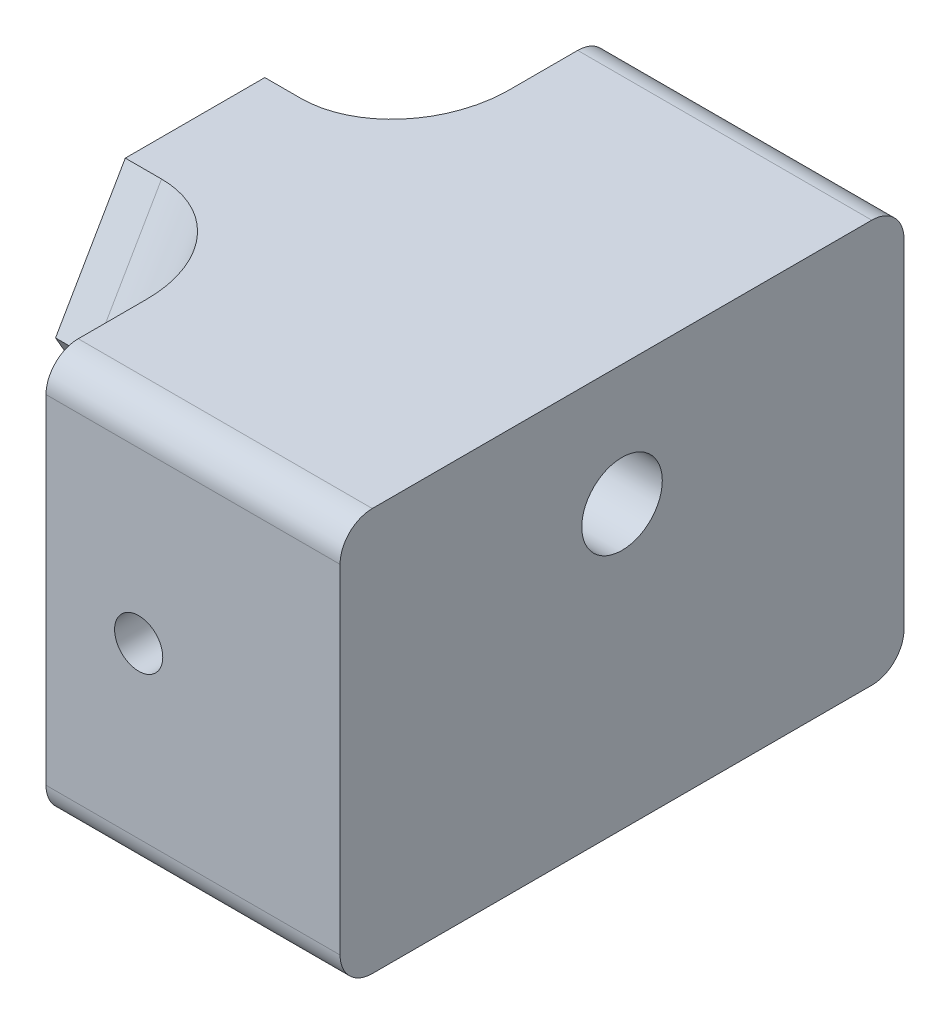
SolidWorks part; units mm, degrees
material "ABS"
ref_plane "Front Plane" through (0, 0, 0) normal (0, 0, 1) x (1, 0, 0)
ref_plane "Top Plane" through (0, 0, 0) normal (0, 1, 0) x (1, 0, 0)
ref_plane "Right Plane" through (0, 0, 0) normal (1, 0, 0) x (0, 0, -1)
sketch "Sketch1" plane through (0, 0, 0) normal (1, 0, 0) x (0, 0, -1)
  line L1 (0, 0) -> (44.45, 0)
  line L2 (0, 0) -> (0, -31.75)
  line L3 (0, -31.75) -> (44.45, -31.75)
  line L4 (44.45, 0) -> (44.45, -31.75)
  dimension "D1" = 44.45
  dimension "D2" = 31.75
extrude "Boss-Extrude1" add sketch "Sketch1" along normal blind 25.4 and the other way blind 8.255
sketch "Sketch2" plane through (-8.255, 0, 0) normal (-1, 0, 0) x (0, 0, 1)
  line L0 (0, 0) -> (0, -31.75) construction
  line L1 (-18.5588, -15.875) -> (-14.8927, -9.525)
  line L2 (-14.8927, -9.525) -> (-18.5588, -3.175)
  line L3 (-18.5588, -3.175) -> (-25.8912, -3.175)
  line L4 (-25.8912, -3.175) -> (-29.5573, -9.525)
  line L5 (-29.5573, -9.525) -> (-25.8912, -15.875)
  line L6 (-25.8912, -15.875) -> (-18.5588, -15.875)
  line L7 (-44.45, 0) -> (0, 0) construction
  circle A0 centre (-22.225, -9.525) radius 6.35 construction
  point P1 (0, -15.875)
  point P13 (-22.225, 0)
  dimension "D1" = 12.7
  dimension "D2" = 9.525
extrude "Cut-Extrude1" cut sketch "Sketch2" against normal blind 7.9375
sketch "Sketch3" plane through (25.4, 0, 0) normal (1, 0, 0) x (0, 0, -1)
  line L0 (44.45, 0) -> (0, 0) construction
  line L1 (0, 0) -> (0, -31.75) construction
  circle A0 centre (22.225, -9.525) radius 3.175
  point P2 (22.225, 0)
  point P3 (0, -15.875)
  dimension "D1" = 6.35
  dimension "D2" = 9.525
extrude "Cut-Extrude2" cut sketch "Sketch3" against normal through all
sketch "Sketch4" plane through (0, 0, 0) normal (0, 0, 1) x (1, 0, 0)
  line L0 (25.4, -15.875) -> (9.525, -15.875) construction
  line L1 (25.4, 0) -> (25.4, -31.75) construction
  circle A2 centre (9.525, -15.875) radius 1.8986
  dimension "D2" = 3.7973
  dimension "D1" = 15.875
ref_plane "Plane1" through (0, 0, -22.225) normal (0, 0, 1) x (1, 0, 0)
extrude "Cut-Extrude4" cut sketch "Sketch4" against normal blind 4.7625
mirror "Mirror3" about plane through (0, 0, -22.225) normal (0, 0, 1) of "Cut-Extrude4"
ref_plane "Plane2" through (25.4, 0, -44.45) normal (-1, 0, 0) x (0, 0, 1)
fillet "Fillet1" radius 2.54 4 edges at (8.5725, -31.75, -44.45) (8.5725, -31.75, 0) (8.5725, 0, -44.45) (8.5725, 0, 0)
sketch "Sketch5" plane through (-8.255, 0, 0) normal (-1, 0, 0) x (0, 0, 1)
  line L4 (-44.45, -2.54) -> (-44.45, -29.21)
  line L5 (-41.91, -31.75) -> (-2.54, -31.75)
  line L6 (0, -29.21) -> (0, -2.54)
  line L7 (-2.54, 0) -> (-41.91, 0)
  line L8 (-44.45, -2.54) -> (-44.45, -29.21)
  line L9 (-41.91, -31.75) -> (-2.54, -31.75)
  line L10 (0, -29.21) -> (0, -2.54)
  line L29 (-41.91, 0) -> (-27.7243, 0)
  line L30 (-16.7257, 0) -> (-2.54, 0)
  line L35 (-33.2235, -9.525) -> (-27.7243, -19.05)
  line L36 (-27.7243, -19.05) -> (-16.7257, -19.05)
  line L37 (-16.7257, -19.05) -> (-11.2265, -9.525)
  line L38 (-11.2265, -9.525) -> (-16.7257, 0)
  line L39 (-16.7257, 0) -> (-27.7243, 0)
  line L40 (-27.7243, 0) -> (-33.2235, -9.525)
  line L41 (-33.2235, -9.525) -> (-27.7243, -19.05)
  line L42 (-27.7243, -19.05) -> (-16.7257, -19.05)
  line L43 (-16.7257, -19.05) -> (-11.2265, -9.525)
  line L44 (-11.2265, -9.525) -> (-16.7257, 0)
  line L46 (-27.7243, 0) -> (-33.2235, -9.525)
  arc A4 (-44.45, -29.21) -> (-41.91, -31.75) centre (-41.91, -29.21) ccw
  arc A5 (-2.54, -31.75) -> (0, -29.21) centre (-2.54, -29.21) ccw
  arc A6 (0, -2.54) -> (-2.54, 0) centre (-2.54, -2.54) ccw
  arc A7 (-41.91, 0) -> (-44.45, -2.54) centre (-41.91, -2.54) ccw
  arc A8 (-44.45, -29.21) -> (-41.91, -31.75) centre (-41.91, -29.21) ccw
  arc A9 (-2.54, -31.75) -> (0, -29.21) centre (-2.54, -29.21) ccw
  arc A10 (0, -2.54) -> (-2.54, 0) centre (-2.54, -2.54) ccw
  arc A11 (-41.91, 0) -> (-44.45, -2.54) centre (-41.91, -2.54) ccw
  dimension "D1" = 0
  dimension "D2" = 3.175
extrude "Cut-Extrude5" cut sketch "Sketch5" against normal blind 10.4775
fillet "Fillet2" radius 7.62 5 edges at (2.2225, -14.2875, -30.4739) (2.2225, -4.7625, -30.4739) (2.2225, -19.05, -22.225) (2.2225, -14.2875, -13.9761) (2.2225, -4.7625, -13.9761)
